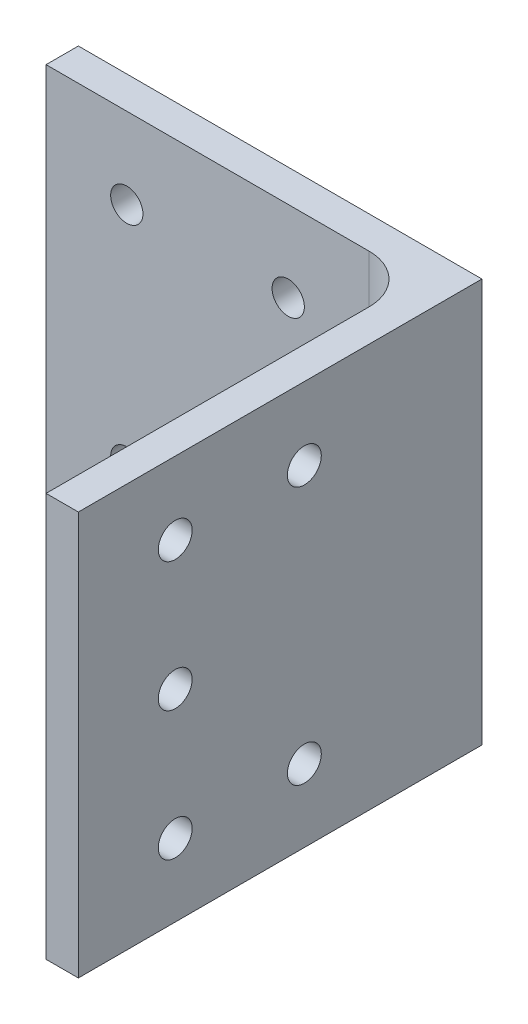
SolidWorks part; units mm, degrees
material "1060 合金"
ref_plane "前视基准面" through (0, 0, 0) normal (0, 0, 1) x (1, 0, 0)
ref_plane "上视基准面" through (0, 0, 0) normal (0, 1, 0) x (1, 0, 0)
ref_plane "右视基准面" through (0, 0, 0) normal (1, 0, 0) x (0, 0, -1)
ref_plane "基准面4" through (0, 0, 25) normal (0, 0, 1) x (1, 0, 0)
sketch "草图1" plane through (0, 0, 25) normal (0, 0, 1) x (1, 0, 0)
  line L0 (-25, 0) -> (0, 0)
  line L1 (0, 0) -> (0, 25)
  line L2 (0, 25) -> (-25, 25)
  line L3 (-25, 25) -> (-25, 0)
extrude "凸台-拉伸1" add sketch "草图1" against normal blind 25
sketch "草图2" plane through (0, 0, 0) normal (0, -1, 0) x (1, 0, 0)
  line L0 (-25, 2) -> (-2, 2)
  line L1 (-2, 2) -> (-2, 25)
  line L2 (-2, 25) -> (-25, 25)
  line L3 (-25, 25) -> (-25, 2)
extrude "切除-拉伸1" cut sketch "草图2" against normal through all
hole_wizard "Ø2.0 (2) 直径孔1" positions "草图4" profile "草图3" hole size "Ø2.0" standard "ANSI Metric"
sketch "草图4" plane through (0, 0, 2) normal (0, 0, 1) x (1, 0, 0)
  point P0 (-10, 20)
  point P1 (-10, 6)
  point P2 (-20, 6)
  point P3 (-20, 19.9883)
sketch "草图3" plane through (-10, 20, 2) normal (1, 0, 0) x (0, -1, 0)
  line L0 (0, 0) -> (0, 2)
  line L1 (0, 2) -> (1, 2)
  line L2 (1, 2) -> (1, 0)
  line L5 (1, 0) -> (0, 0)
  line L11 (0, -6.35) -> (0, 107.95) construction
  dimension "通孔孔直径" = 2
  dimension "通孔孔深度" = 2
hole_wizard "Ø2.1 (2.1) 直径孔1" positions "草图6" profile "草图5" hole size "Ø2.1" standard "ANSI Metric"
sketch "草图6" plane through (0, 0, 0) normal (1, 0, 0) x (0, 0, -1)
  point P0 (-19, 20.5)
  point P1 (-19, 4.5)
  point P2 (-19, 12.5)
  point P3 (-11, 4.5)
  point P4 (-11, 20.5)
sketch "草图5" plane through (0, 20.5, 19) normal (0, 1, 0) x (0, 0, -1)
  line L0 (0, 0) -> (0, 25)
  line L1 (0, 25) -> (1.05, 25)
  line L2 (1.05, 25) -> (1.05, 0)
  line L5 (1.05, 0) -> (0, 0)
  line L11 (0, -6.35) -> (0, 107.95) construction
  dimension "通孔孔直径" = 2.1
  dimension "通孔孔深度" = 25
fillet "圆角1" radius 3 1 edges at (-2, 12.5, 2)
